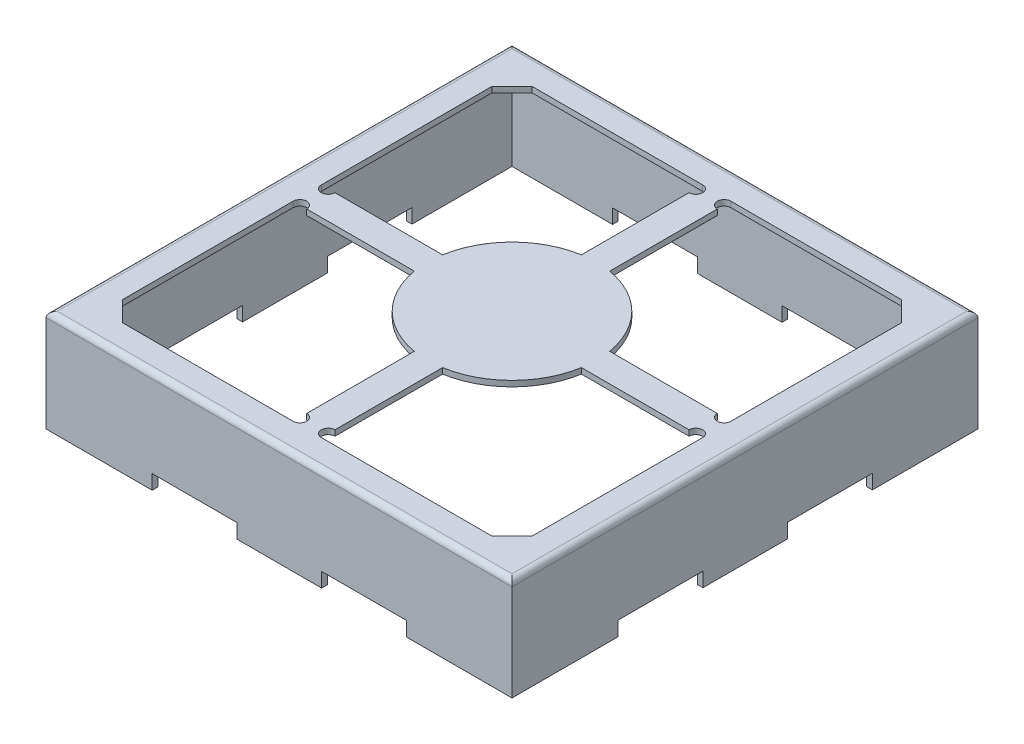
SolidWorks part; units mm, degrees
ref_plane "前视基准面" through (0, 0, 0) normal (0, 0, 1) x (1, 0, 0)
ref_plane "上视基准面" through (0, 0, 0) normal (0, 1, 0) x (1, 0, 0)
ref_plane "右视基准面" through (0, 0, 0) normal (1, 0, 0) x (0, 0, -1)
sketch "草图1" plane through (0, 0, 0) normal (0, 1, 0) x (1, 0, 0)
  line L0 (1, -14.7935) -> (1, -1.7065)
  line L1 (0, 0) -> (16.5, 0)
  line L2 (0, 0) -> (0, -16.5)
  line L3 (0, -8.25) -> (16.5, -8.25)
  line L4 (8.25, 0) -> (8.25, -16.5)
  line L5 (1, -1.7065) -> (1.7065, -1)
  line L6 (1.7065, -1) -> (14.7935, -1)
  line L7 (7.75, -1) -> (7.75, -5.292)
  line L8 (1, -7.75) -> (5.292, -7.75)
  line L9 (0.2, -16.3) -> (0.2, -0.2)
  line L10 (0.2, -0.2) -> (16.3, -0.2)
  line L11 (0.2, -16.3) -> (16.3, -16.3)
  line L12 (1, -8.75) -> (5.292, -8.75)
  line L13 (7.75, -15.5) -> (7.75, -11.208)
  line L14 (1.7065, -15.5) -> (14.7935, -15.5)
  line L15 (1, -14.7935) -> (1.7065, -15.5)
  line L16 (0, -16.5) -> (16.5, -16.5)
  line L17 (15.5, -14.7935) -> (14.7935, -15.5)
  line L18 (8.75, -15.5) -> (8.75, -11.208)
  line L19 (15.5, -8.75) -> (11.208, -8.75)
  line L20 (16.3, -16.3) -> (16.3, -0.2)
  line L21 (15.5, -7.75) -> (11.208, -7.75)
  line L22 (8.75, -1) -> (8.75, -5.292)
  line L23 (15.5, -1.7065) -> (14.7935, -1)
  line L24 (16.5, 0) -> (16.5, -16.5)
  line L25 (15.5, -14.7935) -> (15.5, -1.7065)
  circle A0 centre (8.25, -8.25) radius 3
  arc A1 (1, -7.75) -> (1.48, -7.75) centre (1.24, -7.75) ccw
  arc A2 (1, -8.75) -> (1.48, -8.75) centre (1.24, -8.75) cw
  arc A3 (15.5, -7.75) -> (15.02, -7.75) centre (15.26, -7.75) cw
  arc A4 (15.5, -8.75) -> (15.02, -8.75) centre (15.26, -8.75) ccw
  arc A5 (8.75, -1) -> (8.75, -1.48) centre (8.75, -1.24) ccw
  arc A6 (7.75, -1) -> (7.75, -1.48) centre (7.75, -1.24) cw
  arc A7 (8.75, -15.5) -> (8.75, -15.02) centre (8.75, -15.26) cw
  arc A8 (7.75, -15.5) -> (7.75, -15.02) centre (7.75, -15.26) ccw
  point P20 (0.2, -8.25)
  point P29 (1, -8.25)
  point P31 (8.25, -15.5)
  point P36 (8.25, -16.3)
  point P37 (8.25, -0.2)
  point P42 (8.25, -1)
  point P45 (15.5, -8.25)
  point P46 (16.3, -8.25)
  dimension "D7" = 3
  dimension "D12" = 0.24
  dimension "D13" = 0.24
  dimension "D1" = 8.25
  dimension "D2" = 8.25
  dimension "D3" = 1
  dimension "D4" = 1
  dimension "D5" = 135
  dimension "D6" = 0.9992
  dimension "D8" = 0.5
  dimension "D9" = 0.5
  dimension "D10" = 0.2
  dimension "D11" = 0.2
extrude "凸台-拉伸1" add sketch "草图1" against normal blind 0.2 contours L4 A0 L3 | L3 A0 L4 | L4 A0 L3 | L3 A0 L4 | L10 L9 L3 L0 L5 L6 L4 | A0 L8 L0 L3 | A0 L3 L0 L12 | L15 L0 L3 L9 L11 L4 L14 | A0 L13 L14 L4 | A0 L4 L14 L18 | L25 L17 L14 L4 L11 L20 L3 | A0 L19 L25 L3 | A0 L3 L25 L21 | L25 L3 L20 L10 L4 L6 L23 | A0 L4 L6 L7 | A0 L22 L6 L4
sketch "草图2" plane through (0, 0, 0) normal (0, 1, 0) x (1, 0, 0)
  line L0 (0.2, -0.2) -> (16.3, -0.2) construction
  line L1 (0.2, -0.2) -> (16.3, -0.2)
  line L2 (16.3, -16.3) -> (16.3, -0.2) construction
  line L3 (16.3, -16.3) -> (16.3, -0.2)
  line L4 (0.2, -16.3) -> (0.2, -0.2) construction
  line L5 (0.2, -16.3) -> (0.2, -0.2)
  line L6 (0.2, -16.3) -> (16.3, -16.3) construction
  line L7 (0.2, -16.3) -> (16.3, -16.3)
  line L9 (0, 0) -> (16.5, 0)
  line L10 (0, 0) -> (0, -16.5)
  line L11 (0, -16.5) -> (16.5, -16.5)
  line L12 (16.5, 0) -> (16.5, -16.5)
  line L13 (0, 0) -> (16.5, -16.5) construction
  line L14 (0, -16.5) -> (16.5, 0) construction
  point P4 (8.25, -8.25)
  dimension "D1" = 0.2
  dimension "D2" = 0.2
  dimension "D3" = 0.2
  dimension "D4" = 0.2
extrude "凸台-拉伸2" add sketch "草图2" against normal blind 3.61
fillet "圆角1" radius 0.2 4 edges at (8.25, 0, 16.5) (16.5, 0, 8.25) (8.25, 0, 0) (0, 0, 8.25)
sketch "草图3" plane through (0, -3.61, 0) normal (0, -1, 0) x (1, 0, 0)
  line L0 (0, 12.74) -> (0.2, 12.74)
  line L1 (0, 0) -> (0, 16.5) construction
  line L2 (0.2, 0.2) -> (0.2, 16.3) construction
  line L3 (0, 9.74) -> (0.2, 9.74)
  line L4 (0, 6.74) -> (0.2, 6.74)
  line L5 (0, 3.74) -> (0.2, 3.74)
  line L6 (0, 16.5) -> (16.5, 16.5) construction
  line L7 (0, 12.74) -> (0, 9.74)
  line L8 (0.2, 12.74) -> (0.2, 9.74)
  line L9 (0, 6.74) -> (0, 3.74)
  line L10 (0.2, 6.74) -> (0.2, 3.74)
  line L11 (8.25, 16.3) -> (8.25, 0.2) construction
  line L12 (0.2, 16.3) -> (16.3, 16.3) construction
  line L13 (16.3, 0.2) -> (0.2, 0.2) construction
  line L14 (16.5, 9.74) -> (16.3, 9.74)
  line L15 (16.5, 12.74) -> (16.3, 12.74)
  line L16 (16.5, 3.74) -> (16.3, 3.74)
  line L17 (16.5, 6.74) -> (16.3, 6.74)
  line L18 (16.5, 6.74) -> (16.5, 3.74)
  line L19 (16.3, 6.74) -> (16.3, 3.74)
  line L20 (16.5, 12.74) -> (16.5, 9.74)
  line L21 (16.3, 12.74) -> (16.3, 9.74)
  line L22 (3.76, 16.5) -> (3.76, 16.3)
  line L23 (6.76, 16.5) -> (6.76, 16.3)
  line L24 (9.76, 16.5) -> (9.76, 16.3)
  line L25 (12.76, 16.5) -> (12.76, 16.3)
  line L26 (3.76, 16.3) -> (6.76, 16.3)
  line L27 (6.76, 16.5) -> (3.76, 16.5)
  line L28 (9.76, 16.3) -> (12.76, 16.3)
  line L29 (12.76, 16.5) -> (9.76, 16.5)
  line L30 (0.2, 8.25) -> (16.3, 8.25) construction
  line L31 (16.3, 16.3) -> (16.3, 0.2) construction
  line L32 (9.76, 0) -> (9.76, 0.2)
  line L33 (12.76, 0) -> (12.76, 0.2)
  line L34 (6.76, 0) -> (6.76, 0.2)
  line L35 (3.76, 0) -> (3.76, 0.2)
  line L36 (12.76, 0) -> (9.76, 0)
  line L37 (9.76, 0.2) -> (12.76, 0.2)
  line L38 (6.76, 0) -> (3.76, 0)
  line L39 (3.76, 0.2) -> (6.76, 0.2)
  dimension "D1" = 3.76
  dimension "D2" = 3
  dimension "D3" = 3
  dimension "D4" = 3
  dimension "D5" = 3.76
  dimension "D6" = 3
  dimension "D7" = 3
  dimension "D8" = 3
extrude "切除-拉伸1" cut sketch "草图3" against normal blind 0.51
